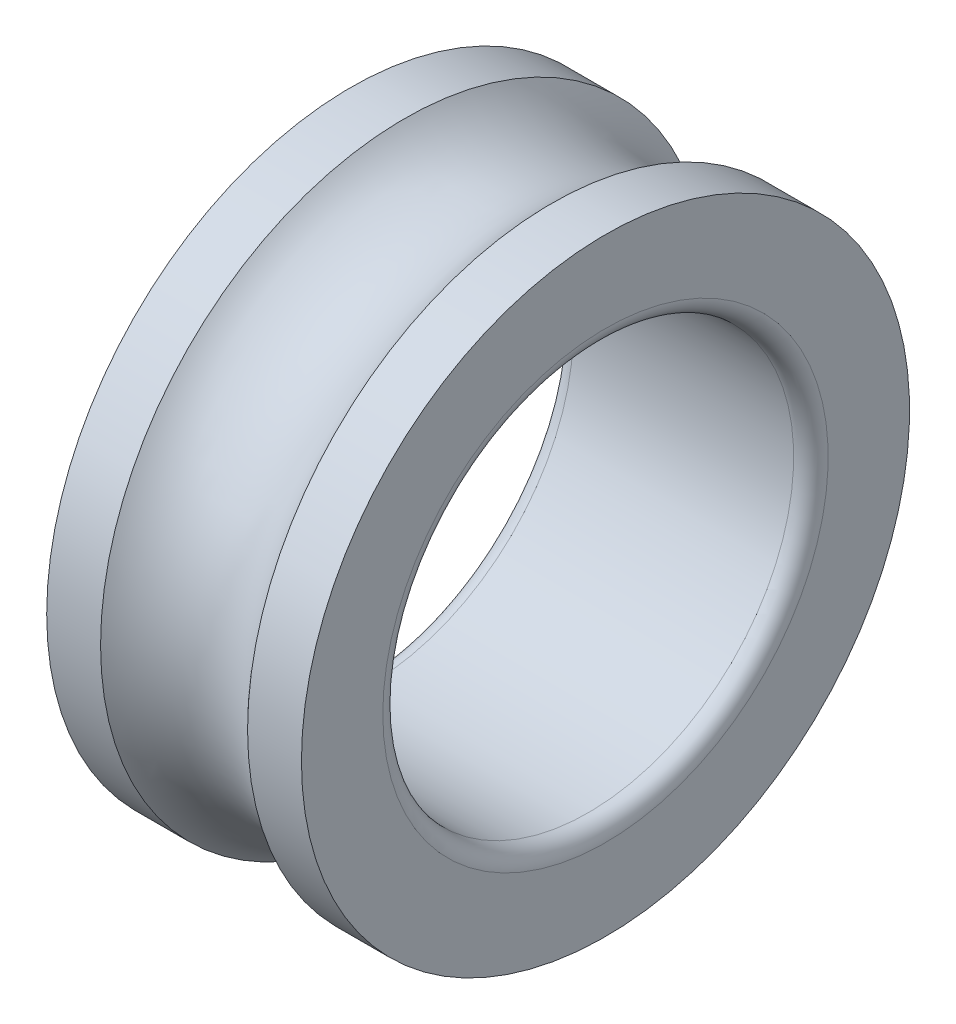
SolidWorks part; units mm, degrees
material "Brass"
ref_plane "Front Plane" through (0, 0, 0) normal (0, 0, 1) x (1, 0, 0)
ref_plane "Top Plane" through (0, 0, 0) normal (0, 1, 0) x (1, 0, 0)
ref_plane "Right Plane" through (0, 0, 0) normal (1, 0, 0) x (0, 0, -1)
sketch "Sketch1" plane through (0, 0, 0) normal (0, 0, 1) x (1, 0, 0)
  line L0 (-31.1422, 0) -> (32.7775, 0) construction
  line L1 (0, 0) -> (0, 25) construction
  line L2 (-15.5, 37) -> (-8.9443, 37)
  line L3 (-15.5, 37) -> (-15.5, 27.1)
  line L4 (-13.4, 25) -> (13.4, 25)
  line L5 (15.5, 37) -> (15.5, 27.1)
  line L6 (-15.5, 37) -> (15.5, 25) construction
  line L7 (-15.5, 25) -> (15.5, 37) construction
  line L8 (8.9443, 37) -> (15.5, 37)
  arc A0 (-8.9443, 37) -> (8.9443, 37) centre (0, 45) ccw
  arc A1 (-13.4, 25) -> (-15.5, 27.1) centre (-13.4, 27.1) cw
  arc A2 (15.5, 27.1) -> (13.4, 25) centre (13.4, 27.1) cw
  point P3 (0, 31)
  dimension "D5" = 12
  dimension "D6" = 2.1
  dimension "D7" = 2.1
  dimension "D1" = 31
  dimension "D2" = 25
  dimension "D3" = 37
  dimension "D4" = 8
revolve "Revolve1" add sketch "Sketch1" angle 360 about L0
scale "Scale1" scale about centroid uniform scaling yes scale factor 0.2
scale "Scale2" scale about centroid uniform scaling yes scale factor 1.9329
scale "Scale3" scale about centroid uniform scaling yes scale factor 1.5
